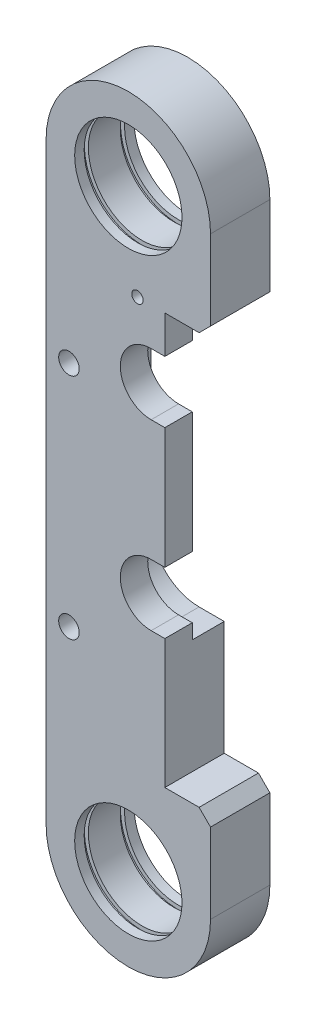
SolidWorks part; units mm, degrees
material "3.3535 (AlMg3) eloxiert"
ref_plane "Vorne" through (0, 0, 0) normal (0, 0, 1) x (1, 0, 0)
ref_plane "Oben" through (0, 0, 0) normal (0, 1, 0) x (1, 0, 0)
ref_plane "Rechts" through (0, 0, 0) normal (1, 0, 0) x (0, 0, -1)
sketch "Skizze1" plane through (0, 0, 0) normal (0, 0, 1) x (1, 0, 0)
  line L0 (31, 90) -> (16, 90)
  line L1 (16, 90) -> (16, -90)
  line L2 (-36, 130) -> (-36, -130)
  line L3 (16, -90) -> (31, -90)
  line L4 (36, 130) -> (36, 95)
  line L5 (36, -95) -> (36, -130)
  line L6 (36, 95) -> (31, 90)
  line L7 (31, -90) -> (36, -95)
  arc A0 (36, 130) -> (-36, 130) centre (0, 130) ccw
  arc A1 (-36, -130) -> (36, -130) centre (0, -130) ccw
  circle A2 centre (0, -130) radius 23.5
  circle A3 centre (0, 130) radius 23.5
  point P13 (36, -90)
  point P17 (16, -90)
  point P20 (16, 90)
  point P22 (36, 90)
  dimension "D1" = 47
  dimension "D2" = 72
  dimension "D3" = 260
  dimension "D4" = 130
  dimension "D5" = 20
  dimension "D7" = 180
  dimension "D8" = 90
extrude "Aufsatz-Linear austragen1" add sketch "Skizze1" along normal blind 26
hole_wizard "Ø9.0 (9) Durchmesser Bohrung1" positions "Skizze4" profile "Skizze3" hole size "Ø9.0" standard "Gabler-Normteile" end condition through all
sketch "Skizze4" plane through (0, 0, 26) normal (0, 0, 1) x (1, 0, 0)
  line L0 (-36, 130) -> (-36, -130) construction
  point P0 (-26, 50)
  point P2 (-26, -50)
  dimension "D1" = 100
  dimension "D2" = 10
  dimension "D3" = 50
sketch "Skizze3" plane through (-26, 50, 26) normal (1, 0, 0) x (0, -1, 0)
  line L0 (0, 0) -> (0, 26)
  line L1 (0, 26) -> (4.5, 26)
  line L2 (4.5, 26) -> (4.5, 0)
  line L5 (4.5, 0) -> (0, 0)
  line L11 (0, -6.35) -> (0, 107.95) construction
  dimension "Bohrerdurchmesser" = 9
  dimension "Bohrungstiefe" = 26
sketch "Skizze5" plane through (0, 0, 0) normal (1, 0, 0) x (0, 0, -1)
  line L0 (-39.74, 130) -> (16.5779, 130) construction
  line L1 (-26, 130) -> (0, 130) construction
  line L2 (-26, 166) -> (-26, 130) construction
  line L3 (-21.85, 155.25) -> (-20, 155.25)
  line L4 (-21.85, 155.25) -> (-21.85, 153.5)
  line L5 (-21.85, 153.5) -> (-20, 153.5)
  line L6 (-20, 155.25) -> (-20, 153.5)
  line L7 (-6, 155.25) -> (-4.15, 155.25)
  line L8 (-6, 155.25) -> (-6, 153.5)
  line L9 (-6, 153.5) -> (-4.15, 153.5)
  line L10 (-4.15, 155.25) -> (-4.15, 153.5)
  dimension "D1" = 14
  dimension "D2" = 6
  dimension "D3" = 50.5
  dimension "D4" = 47
  dimension "D5" = 1.85
revolve "Schnitt-Rotation1" cut sketch "Skizze5" angle 360 about L0
mirror "Spiegeln1" about plane through (0, 0, 0) normal (0, 1, 0) of "Schnitt-Rotation1"
sketch "Skizze6" plane through (0, 0, 0) normal (0, 0, -1) x (-1, 0, 0)
  line L0 (-16, -90) -> (-16, 90) construction
  line L1 (-16, -40) -> (-16, 80)
  line L2 (-16, 80) -> (-5, 80)
  line L3 (16, 59) -> (16, -19)
  line L4 (-5, -40) -> (-16, -40)
  line L5 (36, 130) -> (36, -130) construction
  line L6 (-16, 90) -> (-31, 90) construction
  arc A2 (16, -19) -> (-5, -40) centre (-5, -19) cw
  arc A3 (-5, 80) -> (16, 59) centre (-5, 59) cw
  point P9 (-23.5, 90)
  dimension "D2" = 10
  dimension "D1" = 120
  dimension "D5" = 21
  dimension "D4" = 20
extrude "Schnitt-Linear austragen1" cut sketch "Skizze6" against normal blind 14
hole_wizard "M6 Gewindebohrung1" positions "Skizze8" profile "Skizze7" tap size "M6" standard "Gabler-Normteile"
sketch "Skizze8" plane through (-36, 0, 0) normal (-1, 0, 0) x (0, 0, 1)
  line L1 (26, 130) -> (26, -130) construction
  point P2 (11.4, 63)
  point P11 (11.4, -82)
  dimension "D1" = 8
  dimension "D2" = 145
  dimension "D3" = 14.6
sketch "Skizze7" plane through (-36, 63, 11.4) normal (0, 1, 0) x (0, 0, 1)
  line L0 (0, 0) -> (0, 18.5022)
  line L1 (0, 18.5022) -> (2.5, 17)
  line L2 (2.5, 17) -> (2.5, 0)
  line L5 (2.5, 0) -> (0, 0)
  line L10 (0, 18.5022) -> (-2.5, 17) construction
  line L11 (0, -6.35) -> (0, 107.95) construction
  dimension "Bohrerdurchmesser" = 5
  dimension "Bohrungstiefe" = 17
  dimension "Spitzenwinkel" = 118
cosmetic thread "Bohrungsgewinde1" parameters "D1"=12, "D2"=6
cosmetic thread "Bohrungsgewinde3" parameters "D1"=12, "D2"=6
sketch "Skizze9" plane through (0, 0, 14) normal (0, 0, -1) x (-1, 0, 0)
  line L0 (-10, 73.5) -> (-16, 73.5)
  line L1 (-16, 80) -> (-16, -40) construction
  line L2 (-10, 46.5) -> (-16, 46.5)
  line L3 (-16, 73.5) -> (-16, 46.5)
  line L4 (-10, -6.5) -> (-16, -6.5)
  line L5 (-10, -33.5) -> (-16, -33.5)
  line L6 (-16, -6.5) -> (-16, -33.5)
  arc A0 (-10, 46.5) -> (-10, 73.5) centre (-10, 60) ccw
  circle A1 centre (0, 130) radius 23.5 construction
  arc A2 (-10, -33.5) -> (-10, -6.5) centre (-10, -20) ccw
  circle A3 centre (0, -130) radius 23.5 construction
  dimension "D1" = 27
  dimension "D2" = 70
  dimension "D3" = 110
  dimension "D4" = 80
  dimension "D5" = 6
extrude "Schnitt-Linear austragen2" cut sketch "Skizze9" against normal through all
hole_wizard "M6 Gewindebohrung2" positions "Skizze10" profile "Skizze11" tap size "M6" standard "Gabler-Normteile" end condition through all
sketch "Skizze10" plane through (0, 0, 26) normal (0, 0, 1) x (1, 0, 0)
  line L0 (31, -90) -> (16, -90) construction
  line L1 (-36, 130) -> (-36, -130) construction
  point P0 (4, 90)
  dimension "D1" = 180
  dimension "D2" = 40
sketch "Skizze11" plane through (4, 90, 26) normal (1, 0, 0) x (0, -1, 0)
  line L0 (0, 0) -> (0, 26)
  line L1 (0, 26) -> (2.5, 26)
  line L2 (2.5, 26) -> (2.5, 0)
  line L5 (2.5, 0) -> (0, 0)
  line L11 (0, -6.35) -> (0, 107.95) construction
  dimension "Bohrerdurchmesser" = 5
  dimension "Bohrungstiefe" = 26
cosmetic thread "Bohrungsgewinde4" parameters "D2"=6
